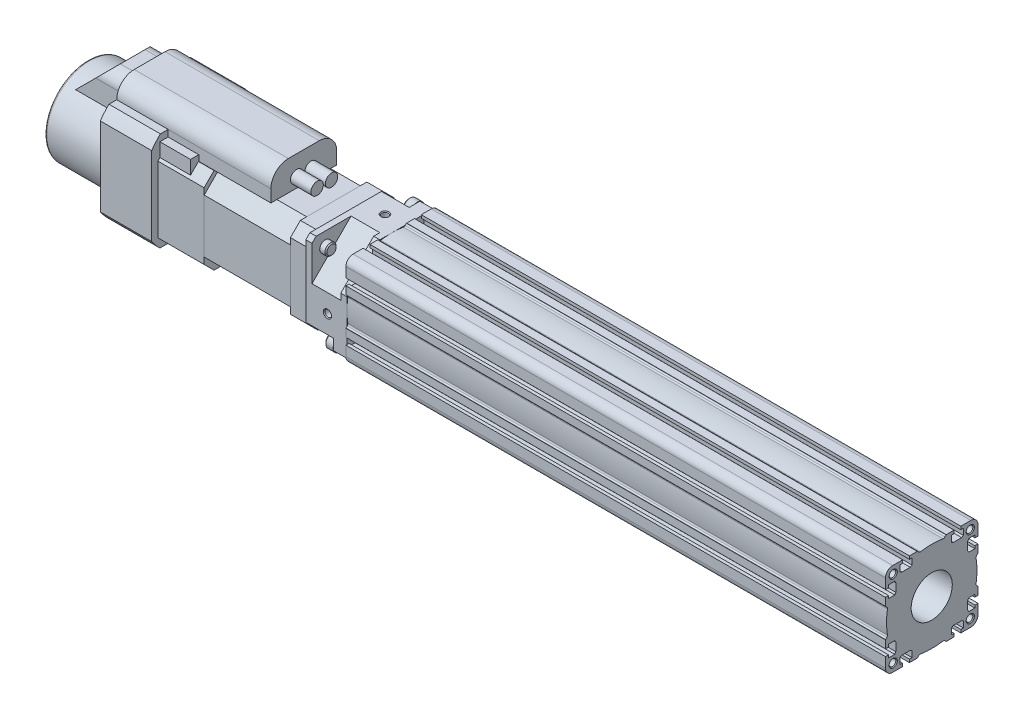
SolidWorks part; units mm, degrees
ref_plane "Front Plane" through (0, 0, 0) normal (0, 0, 1) x (1, 0, 0)
ref_plane "Top Plane" through (0, 0, 0) normal (0, 1, 0) x (1, 0, 0)
ref_plane "Right Plane" through (0, 0, 0) normal (1, 0, 0) x (0, 0, -1)
ref_plane "Plane1" through (0, 0, 0) normal (1, 0, 0) x (0, 0, -1)
sketch "Sketch1" plane through (0, 0, 0) normal (1, 0, 0) x (0, 0, -1)
  line L0 (-19, -22.5) -> (-7.0828, -22.5)
  line L1 (-6.9414, -22.4414) -> (-6.3482, -21.8482)
  line L2 (6.3482, -21.8482) -> (6.9414, -22.4414)
  line L3 (7.0828, -22.5) -> (19, -22.5)
  line L4 (22.5, -19) -> (22.5, -7.0828)
  line L5 (22.4414, -6.9414) -> (21.8482, -6.3482)
  line L6 (21.8482, 6.3482) -> (22.4414, 6.9414)
  line L7 (22.5, 7.0828) -> (22.5, 19)
  line L8 (19, 22.5) -> (7.0828, 22.5)
  line L9 (6.9414, 22.4414) -> (6.3482, 21.8482)
  line L10 (-6.3482, 21.8482) -> (-6.9414, 22.4414)
  line L11 (-7.0828, 22.5) -> (-19, 22.5)
  line L12 (-22.5, 19) -> (-22.5, 7.0828)
  line L13 (-22.4414, 6.9414) -> (-21.8482, 6.3482)
  line L14 (-21.8482, -6.3482) -> (-22.4414, -6.9414)
  line L15 (-22.5, -7.0828) -> (-22.5, -19)
  arc A0 (-22.5, -19) -> (-19, -22.5) centre (-19, -19) ccw
  arc A1 (-7.0828, -22.5) -> (-6.9414, -22.4414) centre (-7.0828, -22.3) ccw
  arc A2 (-6.3482, -21.8482) -> (-5.4844, -21.5676) centre (-5.6411, -22.5553) cw
  arc A3 (-5.4844, -21.5676) -> (5.4844, -21.5676) centre (0, 13) ccw
  arc A4 (5.4844, -21.5676) -> (6.3482, -21.8482) centre (5.6411, -22.5553) cw
  arc A5 (6.9414, -22.4414) -> (7.0828, -22.5) centre (7.0828, -22.3) ccw
  arc A6 (19, -22.5) -> (22.5, -19) centre (19, -19) ccw
  arc A7 (22.5, -7.0828) -> (22.4414, -6.9414) centre (22.3, -7.0828) ccw
  arc A8 (21.8482, -6.3482) -> (21.5676, -5.4844) centre (22.5553, -5.6411) cw
  arc A9 (21.5676, -5.4844) -> (21.5676, 5.4844) centre (-13, 0) ccw
  arc A10 (21.5676, 5.4844) -> (21.8482, 6.3482) centre (22.5553, 5.6411) cw
  arc A11 (22.4414, 6.9414) -> (22.5, 7.0828) centre (22.3, 7.0828) ccw
  arc A12 (22.5, 19) -> (19, 22.5) centre (19, 19) ccw
  arc A13 (7.0828, 22.5) -> (6.9414, 22.4414) centre (7.0828, 22.3) ccw
  arc A14 (6.3482, 21.8482) -> (5.4844, 21.5676) centre (5.6411, 22.5553) cw
  arc A15 (5.4844, 21.5676) -> (-5.4844, 21.5676) centre (0, -13) ccw
  arc A16 (-5.4844, 21.5676) -> (-6.3482, 21.8482) centre (-5.6411, 22.5553) cw
  arc A17 (-6.9414, 22.4414) -> (-7.0828, 22.5) centre (-7.0828, 22.3) ccw
  arc A18 (-19, 22.5) -> (-22.5, 19) centre (-19, 19) ccw
  arc A19 (-22.5, 7.0828) -> (-22.4414, 6.9414) centre (-22.3, 7.0828) ccw
  arc A20 (-21.8482, 6.3482) -> (-21.5676, 5.4844) centre (-22.5553, 5.6411) cw
  arc A21 (-21.5676, 5.4844) -> (-21.5676, -5.4844) centre (13, 0) ccw
  arc A22 (-21.5676, -5.4844) -> (-21.8482, -6.3482) centre (-22.5553, -5.6411) cw
  arc A23 (-22.4414, -6.9414) -> (-22.5, -7.0828) centre (-22.3, -7.0828) ccw
extrude "Boss-Extrude1" add sketch "Sketch1" against normal blind 262.5
ref_plane "Plane2" through (0, 0, 0) normal (1, 0, 0) x (0, 0, -1)
sketch "Sketch2" plane through (0, 0, 0) normal (1, 0, 0) x (0, 0, -1)
  circle A0 centre (0, 0) radius 10
extrude "Cut-Extrude1" cut sketch "Sketch2" against normal blind 165
ref_plane "Plane3" through (0, 0, 0) normal (0, 0.7071, 0.7071) x (1, 0, 0)
sketch "Sketch3" plane through (0, 0, 0) normal (0, 0.7071, 0.7071) x (1, 0, 0)
  line L0 (-14.9359, 26.5) -> (-14, 28.121)
  line L1 (-14, 28.121) -> (-0.379, 28.121)
  line L2 (-0.379, 28.121) -> (0, 28.5)
  line L3 (0, 28.5) -> (0, 26.5)
  line L4 (0, 26.5) -> (-14.9359, 26.5)
  line L5 (0, 26.5) -> (-14.9359, 26.5) construction
revolve "Cut-Revolve1" cut sketch "Sketch3" angle 360 about L5
ref_plane "Plane4" through (0, 0, 0) normal (0, 0.7071, 0.7071) x (1, 0, 0)
sketch "Sketch4" plane through (0, 0, 0) normal (0, 0.7071, 0.7071) x (1, 0, 0)
  line L0 (-14.9359, -26.5) -> (-14, -24.879)
  line L1 (-14, -24.879) -> (-0.379, -24.879)
  line L2 (-0.379, -24.879) -> (0, -24.5)
  line L3 (0, -24.5) -> (0, -26.5)
  line L4 (0, -26.5) -> (-14.9359, -26.5)
  line L5 (0, -26.5) -> (-14.9359, -26.5) construction
revolve "Cut-Revolve2" cut sketch "Sketch4" angle 360 about L5
ref_plane "Plane5" through (0, 0, 0) normal (0, -0.7071, 0.7071) x (1, 0, 0)
sketch "Sketch5" plane through (0, 0, 0) normal (0, -0.7071, 0.7071) x (1, 0, 0)
  line L0 (-14.9359, 26.5) -> (-14, 28.121)
  line L1 (-14, 28.121) -> (-0.379, 28.121)
  line L2 (-0.379, 28.121) -> (0, 28.5)
  line L3 (0, 28.5) -> (0, 26.5)
  line L4 (0, 26.5) -> (-14.9359, 26.5)
  line L5 (0, 26.5) -> (-14.9359, 26.5) construction
revolve "Cut-Revolve3" cut sketch "Sketch5" angle 360 about L5
ref_plane "Plane6" through (0, 0, 0) normal (0, -0.7071, 0.7071) x (1, 0, 0)
sketch "Sketch6" plane through (0, 0, 0) normal (0, -0.7071, 0.7071) x (1, 0, 0)
  line L0 (-14.9359, -26.5) -> (-14, -24.879)
  line L1 (-14, -24.879) -> (-0.379, -24.879)
  line L2 (-0.379, -24.879) -> (0, -24.5)
  line L3 (0, -24.5) -> (0, -26.5)
  line L4 (0, -26.5) -> (-14.9359, -26.5)
  line L5 (0, -26.5) -> (-14.9359, -26.5) construction
revolve "Cut-Revolve4" cut sketch "Sketch6" angle 360 about L5
ref_plane "Plane7" through (0, 0, 0) normal (1, 0, 0) x (0, 0, -1)
sketch "Sketch7" plane through (0, 0, 0) normal (1, 0, 0) x (0, 0, -1)
  line L0 (-15.4, -21) -> (-14.15, -21)
  line L1 (-14.15, -21) -> (-14.15, -22.5)
  line L2 (-14.15, -22.5) -> (-10.85, -22.5)
  line L3 (-10.85, -22.5) -> (-10.85, -21)
  line L4 (-10.85, -21) -> (-9.6, -21)
  line L5 (-9.6, -21) -> (-9.6, -18)
  line L6 (-9.6, -18) -> (-10.466, -17.5)
  line L7 (-10.466, -17.5) -> (-14.534, -17.5)
  line L8 (-14.534, -17.5) -> (-15.4, -18)
  line L9 (-15.4, -18) -> (-15.4, -21)
extrude "Cut-Extrude2" cut sketch "Sketch7" against normal blind 262.5
ref_plane "Plane8" through (0, 0, 0) normal (1, 0, 0) x (0, 0, -1)
sketch "Sketch8" plane through (0, 0, 0) normal (1, 0, 0) x (0, 0, -1)
  line L0 (9.6, -21) -> (10.85, -21)
  line L1 (10.85, -21) -> (10.85, -22.5)
  line L2 (10.85, -22.5) -> (14.15, -22.5)
  line L3 (14.15, -22.5) -> (14.15, -21)
  line L4 (14.15, -21) -> (15.4, -21)
  line L5 (15.4, -21) -> (15.4, -18)
  line L6 (15.4, -18) -> (14.534, -17.5)
  line L7 (14.534, -17.5) -> (10.466, -17.5)
  line L8 (10.466, -17.5) -> (9.6, -18)
  line L9 (9.6, -18) -> (9.6, -21)
extrude "Cut-Extrude3" cut sketch "Sketch8" against normal blind 262.5
ref_plane "Plane9" through (0, 0, 0) normal (1, 0, 0) x (0, 0, -1)
sketch "Sketch9" plane through (0, 0, 0) normal (1, 0, 0) x (0, 0, -1)
  line L0 (-15.4, 21) -> (-15.4, 18)
  line L1 (-15.4, 18) -> (-14.534, 17.5)
  line L2 (-14.534, 17.5) -> (-10.466, 17.5)
  line L3 (-10.466, 17.5) -> (-9.6, 18)
  line L4 (-9.6, 18) -> (-9.6, 21)
  line L5 (-9.6, 21) -> (-10.85, 21)
  line L6 (-10.85, 21) -> (-10.85, 22.5)
  line L7 (-10.85, 22.5) -> (-14.15, 22.5)
  line L8 (-14.15, 22.5) -> (-14.15, 21)
  line L9 (-14.15, 21) -> (-15.4, 21)
extrude "Cut-Extrude4" cut sketch "Sketch9" against normal blind 262.5
ref_plane "Plane10" through (0, 0, 0) normal (1, 0, 0) x (0, 0, -1)
sketch "Sketch10" plane through (0, 0, 0) normal (1, 0, 0) x (0, 0, -1)
  line L0 (9.6, 21) -> (9.6, 18)
  line L1 (9.6, 18) -> (10.466, 17.5)
  line L2 (10.466, 17.5) -> (14.534, 17.5)
  line L3 (14.534, 17.5) -> (15.4, 18)
  line L4 (15.4, 18) -> (15.4, 21)
  line L5 (15.4, 21) -> (14.15, 21)
  line L6 (14.15, 21) -> (14.15, 22.5)
  line L7 (14.15, 22.5) -> (10.85, 22.5)
  line L8 (10.85, 22.5) -> (10.85, 21)
  line L9 (10.85, 21) -> (9.6, 21)
extrude "Cut-Extrude5" cut sketch "Sketch10" against normal blind 262.5
ref_plane "Plane11" through (0, 0, 0) normal (1, 0, 0) x (0, 0, -1)
sketch "Sketch11" plane through (0, 0, 0) normal (1, 0, 0) x (0, 0, -1)
  line L0 (17.5, -14.534) -> (18, -15.4)
  line L1 (18, -15.4) -> (21, -15.4)
  line L2 (21, -15.4) -> (21, -14.15)
  line L3 (21, -14.15) -> (22.5, -14.15)
  line L4 (22.5, -14.15) -> (22.5, -10.85)
  line L5 (22.5, -10.85) -> (21, -10.85)
  line L6 (21, -10.85) -> (21, -9.6)
  line L7 (21, -9.6) -> (18, -9.6)
  line L8 (18, -9.6) -> (17.5, -10.466)
  line L9 (17.5, -10.466) -> (17.5, -14.534)
extrude "Cut-Extrude6" cut sketch "Sketch11" against normal blind 262.5
ref_plane "Plane12" through (0, 0, 0) normal (1, 0, 0) x (0, 0, -1)
sketch "Sketch12" plane through (0, 0, 0) normal (1, 0, 0) x (0, 0, -1)
  line L0 (17.5, 10.466) -> (18, 9.6)
  line L1 (18, 9.6) -> (21, 9.6)
  line L2 (21, 9.6) -> (21, 10.85)
  line L3 (21, 10.85) -> (22.5, 10.85)
  line L4 (22.5, 10.85) -> (22.5, 14.15)
  line L5 (22.5, 14.15) -> (21, 14.15)
  line L6 (21, 14.15) -> (21, 15.4)
  line L7 (21, 15.4) -> (18, 15.4)
  line L8 (18, 15.4) -> (17.5, 14.534)
  line L9 (17.5, 14.534) -> (17.5, 10.466)
extrude "Cut-Extrude7" cut sketch "Sketch12" against normal blind 262.5
ref_plane "Plane13" through (0, 0, 0) normal (1, 0, 0) x (0, 0, -1)
sketch "Sketch13" plane through (0, 0, 0) normal (1, 0, 0) x (0, 0, -1)
  line L0 (-22.5, 14.15) -> (-22.5, 10.85)
  line L1 (-22.5, 10.85) -> (-21, 10.85)
  line L2 (-21, 10.85) -> (-21, 9.6)
  line L3 (-21, 9.6) -> (-18, 9.6)
  line L4 (-18, 9.6) -> (-17.5, 10.466)
  line L5 (-17.5, 10.466) -> (-17.5, 14.534)
  line L6 (-17.5, 14.534) -> (-18, 15.4)
  line L7 (-18, 15.4) -> (-21, 15.4)
  line L8 (-21, 15.4) -> (-21, 14.15)
  line L9 (-21, 14.15) -> (-22.5, 14.15)
extrude "Cut-Extrude8" cut sketch "Sketch13" against normal blind 262.5
ref_plane "Plane14" through (0, 0, 0) normal (1, 0, 0) x (0, 0, -1)
sketch "Sketch14" plane through (0, 0, 0) normal (1, 0, 0) x (0, 0, -1)
  line L0 (-22.5, -10.85) -> (-22.5, -14.15)
  line L1 (-22.5, -14.15) -> (-21, -14.15)
  line L2 (-21, -14.15) -> (-21, -15.4)
  line L3 (-21, -15.4) -> (-18, -15.4)
  line L4 (-18, -15.4) -> (-17.5, -14.534)
  line L5 (-17.5, -14.534) -> (-17.5, -10.466)
  line L6 (-17.5, -10.466) -> (-18, -9.6)
  line L7 (-18, -9.6) -> (-21, -9.6)
  line L8 (-21, -9.6) -> (-21, -10.85)
  line L9 (-21, -10.85) -> (-22.5, -10.85)
extrude "Cut-Extrude9" cut sketch "Sketch14" against normal blind 262.5
ref_plane "Plane15" through (-262.5, 0, 0) normal (1, 0, 0) x (0, 0, -1)
sketch "Sketch15" plane through (-262.5, 0, 0) normal (1, 0, 0) x (0, 0, -1)
  line L0 (-22, -20) -> (-20, -22)
  line L1 (-20, -22) -> (20, -22)
  line L2 (20, -22) -> (22, -20)
  line L3 (22, -20) -> (22, 20)
  line L4 (22, 20) -> (20, 22)
  line L5 (20, 22) -> (-20, 22)
  line L6 (-20, 22) -> (-22, 20)
  line L7 (-22, 20) -> (-22, -20)
extrude "Boss-Extrude2" add sketch "Sketch15" against normal blind 20
ref_plane "Plane16" through (-269, 0, 0) normal (1, 0, 0) x (0, 0, -1)
sketch "Sketch16" plane through (-269, 0, 0) normal (1, 0, 0) x (0, 0, -1)
  line L0 (14.75, 22) -> (14.75, 18.75)
  line L1 (18.75, 14.75) -> (22, 14.75)
  line L2 (22, 14.75) -> (22, 22)
  line L3 (22, 22) -> (14.75, 22)
  arc A0 (14.75, 18.75) -> (18.75, 14.75) centre (18.75, 18.75) ccw
extrude "Cut-Extrude10" cut sketch "Sketch16" against normal blind 13.5
ref_plane "Plane17" through (-269, 0, 0) normal (1, 0, 0) x (0, 0, -1)
sketch "Sketch17" plane through (-269, 0, 0) normal (1, 0, 0) x (0, 0, -1)
  line L0 (-22, -22) -> (-14.75, -22)
  line L1 (-14.75, -22) -> (-14.75, -18.75)
  line L2 (-18.75, -14.75) -> (-22, -14.75)
  line L3 (-22, -14.75) -> (-22, -22)
  arc A0 (-14.75, -18.75) -> (-18.75, -14.75) centre (-18.75, -18.75) ccw
extrude "Cut-Extrude11" cut sketch "Sketch17" against normal blind 13.5
ref_plane "Plane18" through (-265.5, 0, 0) normal (1, 0, 0) x (0, 0, -1)
sketch "Sketch18" plane through (-265.5, 0, 0) normal (1, 0, 0) x (0, 0, -1)
  line L0 (-25, 25) -> (-25, -25)
  line L1 (-25, -25) -> (25, -25)
  line L2 (25, -25) -> (25, 25)
  line L3 (25, 25) -> (-25, 25)
  line L4 (-22, -22) -> (3, -22)
  line L5 (3, -22) -> (22, -3)
  line L6 (22, -3) -> (22, 22)
  line L7 (22, 22) -> (-3, 22)
  line L8 (-3, 22) -> (-22, 3)
  line L9 (-22, 3) -> (-22, -22)
extrude "Cut-Extrude12" cut sketch "Sketch18" against normal blind 14
ref_plane "Plane19" through (-265.5, 0, 0) normal (1, 0, 0) x (0, 0, -1)
sketch "Sketch19" plane through (-265.5, 0, 0) normal (1, 0, 0) x (0, 0, -1)
  line L0 (-25, 25) -> (-25, -25)
  line L1 (-25, -25) -> (25, -25)
  line L2 (25, -25) -> (25, 25)
  line L3 (25, 25) -> (-25, 25)
  line L4 (-22, -22) -> (6, -22)
  line L5 (6, -22) -> (22, -6)
  line L6 (22, -6) -> (22, 22)
  line L7 (22, 22) -> (-6, 22)
  line L8 (-6, 22) -> (-22, 6)
  line L9 (-22, 6) -> (-22, -22)
extrude "Cut-Extrude13" cut sketch "Sketch19" along normal blind 3
ref_plane "Plane20" through (0, 0, 15.5) normal (0, 0, 1) x (1, 0, 0)
sketch "Sketch20" plane through (0, 0, 15.5) normal (0, 0, 1) x (1, 0, 0)
  line L0 (-279.5, 15.5) -> (-279.5, 18.25)
  line L1 (-279.5, 18.25) -> (-277, 18.25)
  line L2 (-277, 18.25) -> (-276.5, 17.75)
  line L3 (-276.5, 17.75) -> (-276.5, 15.5)
  line L4 (-276.5, 15.5) -> (-279.5, 15.5)
  line L5 (-276.5, 15.5) -> (-279.5, 15.5) construction
revolve "Revolve1" add sketch "Sketch20" angle 360 about L5
ref_plane "Plane21" through (0, 0, -15.5) normal (0, 0, 1) x (1, 0, 0)
sketch "Sketch21" plane through (0, 0, -15.5) normal (0, 0, 1) x (1, 0, 0)
  line L0 (-279.5, -15.5) -> (-279.5, -12.75)
  line L1 (-279.5, -12.75) -> (-277, -12.75)
  line L2 (-277, -12.75) -> (-276.5, -13.25)
  line L3 (-276.5, -13.25) -> (-276.5, -15.5)
  line L4 (-276.5, -15.5) -> (-279.5, -15.5)
  line L5 (-276.5, -15.5) -> (-279.5, -15.5) construction
revolve "Revolve2" add sketch "Sketch21" angle 360 about L5
ref_plane "Plane22" through (0, 0, 0) normal (0, 0.7071, 0.7071) x (1, 0, 0)
sketch "Sketch22" plane through (0, 0, 0) normal (0, 0.7071, 0.7071) x (1, 0, 0)
  line L0 (-273, 26.5) -> (-273, 29.5)
  line L1 (-273, 29.5) -> (-272.5, 30)
  line L2 (-272.5, 30) -> (-269, 30)
  line L3 (-269, 30) -> (-269, 26.5)
  line L4 (-269, 26.5) -> (-273, 26.5)
  line L5 (-269, 26.5) -> (-273, 26.5) construction
revolve "Revolve3" add sketch "Sketch22" angle 360 about L5
ref_plane "Plane23" through (0, 0, 0) normal (0, 0.7071, 0.7071) x (1, 0, 0)
sketch "Sketch23" plane through (0, 0, 0) normal (0, 0.7071, 0.7071) x (1, 0, 0)
  line L0 (-273, -26.5) -> (-273, -23.5)
  line L1 (-273, -23.5) -> (-272.5, -23)
  line L2 (-272.5, -23) -> (-269, -23)
  line L3 (-269, -23) -> (-269, -26.5)
  line L4 (-269, -26.5) -> (-273, -26.5)
  line L5 (-269, -26.5) -> (-273, -26.5) construction
revolve "Revolve4" add sketch "Sketch23" angle 360 about L5
ref_plane "Plane24" through (-272, 0, 0) normal (1, 0, 0) x (0, 0, -1)
sketch "Sketch24" plane through (-272, 0, 0) normal (1, 0, 0) x (0, 0, -1)
  line L0 (6, 22) -> (8, 22)
  line L1 (8, 22) -> (7.621, 21.621)
  line L2 (7.621, 21.621) -> (7.621, 15)
  line L3 (7.621, 15) -> (6, 14.0641)
  line L4 (6, 14.0641) -> (6, 22)
  line L5 (6, 14.0641) -> (6, 22) construction
revolve "Cut-Revolve5" cut sketch "Sketch24" angle 360 about L5
ref_plane "Plane25" through (-272, 0, 0) normal (1, 0, 0) x (0, 0, -1)
sketch "Sketch25" plane through (-272, 0, 0) normal (1, 0, 0) x (0, 0, -1)
  line L0 (-22, -6) -> (-22, -4)
  line L1 (-22, -4) -> (-21.621, -4.379)
  line L2 (-21.621, -4.379) -> (-15, -4.379)
  line L3 (-15, -4.379) -> (-14.0641, -6)
  line L4 (-14.0641, -6) -> (-22, -6)
  line L5 (-14.0641, -6) -> (-22, -6) construction
revolve "Cut-Revolve6" cut sketch "Sketch25" angle 360 about L5
ref_plane "Plane26" through (-272, 0, 0) normal (1, 0, 0) x (0, 0, -1)
sketch "Sketch26" plane through (-272, 0, 0) normal (1, 0, 0) x (0, 0, -1)
  line L0 (22, 6) -> (22, 4)
  line L1 (22, 4) -> (21.621, 4.379)
  line L2 (21.621, 4.379) -> (15, 4.379)
  line L3 (15, 4.379) -> (14.0641, 6)
  line L4 (14.0641, 6) -> (22, 6)
  line L5 (14.0641, 6) -> (22, 6) construction
revolve "Cut-Revolve7" cut sketch "Sketch26" angle 360 about L5
ref_plane "Plane27" through (-282.5, 0, 0) normal (1, 0, 0) x (0, 0, -1)
sketch "Sketch27" plane through (-282.5, 0, 0) normal (1, 0, 0) x (0, 0, -1)
  line L0 (-21, 16.16) -> (-21, -16.16)
  line L1 (-21, -16.16) -> (-16.16, -21)
  line L2 (-16.16, -21) -> (16.16, -21)
  line L3 (16.16, -21) -> (21, -16.16)
  line L4 (21, -16.16) -> (21, 16.16)
  line L5 (21, 16.16) -> (16.16, 21)
  line L6 (16.16, 21) -> (-16.16, 21)
  line L7 (-16.16, 21) -> (-21, 16.16)
extrude "Boss-Extrude3" add sketch "Sketch27" against normal blind 8.5
ref_plane "Plane28" through (-291, 0, 0) normal (1, 0, 0) x (0, 0, -1)
sketch "Sketch28" plane through (-291, 0, 0) normal (1, 0, 0) x (0, 0, -1)
  line L0 (-20.95, -13.05) -> (-13.05, -20.95)
  line L1 (-13.05, -20.95) -> (13.05, -20.95)
  line L2 (13.05, -20.95) -> (20.95, -13.05)
  line L3 (20.95, -13.05) -> (20.95, 13.05)
  line L4 (20.95, 13.05) -> (13.05, 20.95)
  line L5 (13.05, 20.95) -> (-13.05, 20.95)
  line L6 (-13.05, 20.95) -> (-20.95, 13.05)
  line L7 (-20.95, 13.05) -> (-20.95, -13.05)
extrude "Boss-Extrude4" add sketch "Sketch28" against normal blind 42
ref_plane "Plane29" through (-333, 0, 0) normal (1, 0, 0) x (0, 0, -1)
sketch "Sketch29" plane through (-333, 0, 0) normal (1, 0, 0) x (0, 0, -1)
  line L0 (-21, 16.16) -> (-21, -16.16)
  line L1 (-21, -16.16) -> (-16.16, -21)
  line L2 (-16.16, -21) -> (16.16, -21)
  line L3 (16.16, -21) -> (21, -16.16)
  line L4 (21, -16.16) -> (21, 16.16)
  line L5 (21, 16.16) -> (16.16, 21)
  line L6 (16.16, 21) -> (-16.16, 21)
  line L7 (-16.16, 21) -> (-21, 16.16)
extrude "Boss-Extrude5" add sketch "Sketch29" against normal blind 22.5
ref_plane "Plane30" through (-355.5, 0, 0) normal (1, 0, 0) x (0, 0, -1)
sketch "Sketch30" plane through (-355.5, 0, 0) normal (1, 0, 0) x (0, 0, -1)
  line L0 (-22, 22) -> (-22, -22)
  line L1 (-22, -22) -> (22, -22)
  line L2 (22, -22) -> (22, 22)
  line L3 (22, 22) -> (-22, 22)
  line L4 (-20.95, -16.11) -> (-16.11, -20.95)
  line L5 (-16.11, -20.95) -> (16.11, -20.95)
  line L6 (16.11, -20.95) -> (20.95, -16.11)
  line L7 (20.95, -16.11) -> (20.95, 16.11)
  line L8 (20.95, 16.11) -> (16.11, 20.95)
  line L9 (16.11, 20.95) -> (-16.11, 20.95)
  line L10 (-16.11, 20.95) -> (-20.95, 16.11)
  line L11 (-20.95, 16.11) -> (-20.95, -16.11)
extrude "Cut-Extrude14" cut sketch "Sketch30" along normal blind 0.05
ref_plane "Plane31" through (-355.5, 0, 0) normal (1, 0, 0) x (0, 0, -1)
sketch "Sketch31" plane through (-355.5, 0, 0) normal (1, 0, 0) x (0, 0, -1)
  line L0 (-20, -21) -> (20, -21)
  line L1 (24, -16.2788) -> (24, 22.0688)
  line L2 (19.7772, 27) -> (-19.7772, 27)
  line L3 (-24, 22.0688) -> (-24, -16.2788)
  arc A0 (-24, -16.2788) -> (-20, -21) centre (0, 0) ccw
  arc A1 (20, -21) -> (24, -16.2788) centre (0, 0) ccw
  arc A2 (24, 22.0688) -> (19.7772, 27) centre (0, 5.79) ccw
  arc A3 (-19.7772, 27) -> (-24, 22.0688) centre (0, 5.79) ccw
extrude "Boss-Extrude6" add sketch "Sketch31" against normal blind 25
ref_plane "Plane32" through (0, 0, 0) normal (0, 0, 1) x (1, 0, 0)
sketch "Sketch32" plane through (0, 0, 0) normal (0, 0, 1) x (1, 0, 0)
  line L0 (-410.5, 0) -> (-410.5, 20)
  line L1 (-409.5, 21) -> (-370.5, 21)
  line L2 (-370.5, 21) -> (-370.5, 0)
  line L3 (-370.5, 0) -> (-410.5, 0)
  line L4 (-370.5, 0) -> (-410.5, 0) construction
  arc A0 (-410.5, 20) -> (-409.5, 21) centre (-409.5, 20) cw
revolve "Revolve5" add sketch "Sketch32" angle 360 about L4
ref_plane "Plane33" through (0, 0, 0) normal (0, 0, 1) x (1, 0, 0)
sketch "Sketch33" plane through (0, 0, 0) normal (0, 0, 1) x (1, 0, 0)
  line L0 (-406.73, 15) -> (-380.5, 15)
  line L1 (-380.5, 15) -> (-380.5, 33)
  line L2 (-380.5, 33) -> (-388.73, 33)
  line L3 (-388.73, 33) -> (-406.73, 15)
extrude "Boss-Extrude7" add sketch "Sketch33" against normal blind 12 and the other way blind 12
ref_plane "Plane34" through (-380.5, 0, 0) normal (1, 0, 0) x (0, 0, -1)
sketch "Sketch34" plane through (-380.5, 0, 0) normal (1, 0, 0) x (0, 0, -1)
  line L0 (-17, 38) -> (-17, 27)
  line L1 (-17, 27) -> (-12, 27)
  line L2 (-6, 33) -> (6, 33)
  line L3 (12, 27) -> (17, 27)
  line L4 (17, 27) -> (17, 38)
  line L5 (17, 38) -> (-17, 38)
  arc A0 (-12, 27) -> (-6, 33) centre (-6, 27) cw
  arc A1 (6, 33) -> (12, 27) centre (6, 27) cw
extrude "Cut-Extrude15" cut sketch "Sketch34" against normal blind 30
ref_plane "Plane35" through (0, 0, 0) normal (0, 0, 1) x (1, 0, 0)
sketch "Sketch35" plane through (0, 0, 0) normal (0, 0, 1) x (1, 0, 0)
  line L0 (-380.5, 21) -> (-305.5, 21)
  line L1 (-305.5, 21) -> (-305.5, 35.5)
  line L2 (-305.5, 35.5) -> (-380.5, 35.5)
  line L3 (-380.5, 35.5) -> (-380.5, 21)
extrude "Boss-Extrude8" add sketch "Sketch35" against normal blind 16 and the other way blind 16
ref_plane "Plane36" through (-380.5, 0, 0) normal (1, 0, 0) x (0, 0, -1)
sketch "Sketch36" plane through (-380.5, 0, 0) normal (1, 0, 0) x (0, 0, -1)
  line L0 (-21, 40.5) -> (-21, 27)
  line L1 (-21, 27) -> (-16, 27)
  line L2 (-7.5, 35.5) -> (7.5, 35.5)
  line L3 (16, 27) -> (21, 27)
  line L4 (21, 27) -> (21, 40.5)
  line L5 (21, 40.5) -> (-21, 40.5)
  arc A0 (-16, 27) -> (-7.5, 35.5) centre (-7.5, 27) cw
  arc A1 (7.5, 35.5) -> (16, 27) centre (7.5, 27) cw
extrude "Cut-Extrude16" cut sketch "Sketch36" along normal blind 75
ref_plane "Plane37" through (0, 0, 0) normal (0, 0, 1) x (1, 0, 0)
sketch "Sketch37" plane through (0, 0, 0) normal (0, 0, 1) x (1, 0, 0)
  line L0 (-355.5, 23.8) -> (-355.5, 0)
  line L1 (-355.5, 0) -> (-340.6, 0)
  line L2 (-340.6, 0) -> (-340.6, 23.8)
  line L3 (-340.6, 23.8) -> (-355.5, 23.8)
extrude "Boss-Extrude9" add sketch "Sketch37" against normal blind 20 and the other way blind 20
ref_plane "Plane38" through (0, 0, 3.5) normal (0, 0, 1) x (1, 0, 0)
sketch "Sketch38" plane through (0, 0, 3.5) normal (0, 0, 1) x (1, 0, 0)
  line L0 (-305.5, 25.91) -> (-305.5, 28.91)
  line L1 (-305.5, 28.91) -> (-295.5, 28.91)
  line L2 (-295.5, 28.91) -> (-295.5, 25.91)
  line L3 (-295.5, 25.91) -> (-305.5, 25.91)
  line L4 (-295.5, 25.91) -> (-305.5, 25.91) construction
revolve "Revolve6" add sketch "Sketch38" angle 360 about L4
ref_plane "Plane39" through (0, 0, -3.5) normal (0, 0, 1) x (1, 0, 0)
sketch "Sketch39" plane through (0, 0, -3.5) normal (0, 0, 1) x (1, 0, 0)
  line L0 (-305.5, 25.91) -> (-305.5, 28.91)
  line L1 (-305.5, 28.91) -> (-295.5, 28.91)
  line L2 (-295.5, 28.91) -> (-295.5, 25.91)
  line L3 (-295.5, 25.91) -> (-305.5, 25.91)
  line L4 (-295.5, 25.91) -> (-305.5, 25.91) construction
revolve "Revolve7" add sketch "Sketch39" angle 360 about L4
